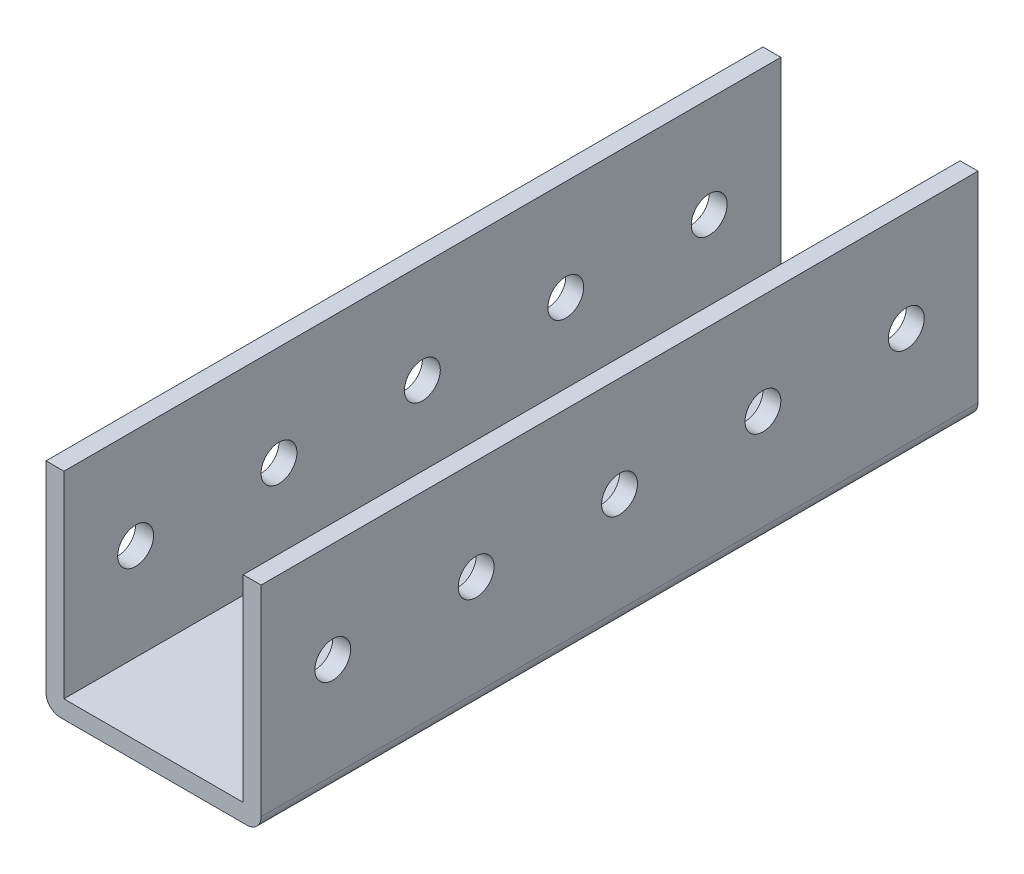
SolidWorks part; units mm, degrees
ref_plane "Front Plane" through (0, 0, 0) normal (0, 0, 1) x (1, 0, 0)
ref_plane "Top Plane" through (0, 0, 0) normal (0, 1, 0) x (1, 0, 0)
ref_plane "Right Plane" through (0, 0, 0) normal (1, 0, 0) x (0, 0, -1)
sketch "Sketch2" plane through (0, 0, 0) normal (0, 1, 0) x (1, 0, 0)
  line L1 (-19.05, -63.5) -> (19.05, -63.5)
  line L2 (-19.05, -63.5) -> (-19.05, 63.5)
  line L3 (-19.05, 63.5) -> (19.05, 63.5)
  line L4 (19.05, -63.5) -> (19.05, 63.5)
  line L5 (-19.05, -63.5) -> (19.05, 63.5) construction
  line L6 (-19.05, 63.5) -> (19.05, -63.5) construction
  point P0 (0, 0)
  dimension "D1" = 38.1
  dimension "D2" = 127
extrude "Boss-Extrude1" add sketch "Sketch2" along normal blind 38.1
sketch "Sketch3" plane through (0, 0, 63.5) normal (0, 0, 1) x (1, 0, 0)
  line L0 (-19.05, 38.1) -> (19.05, 38.1) construction
  line L1 (-15.875, 38.1) -> (15.875, 38.1)
  line L2 (-15.875, 38.1) -> (-15.875, 3.175)
  line L3 (-15.875, 3.175) -> (15.875, 3.175)
  line L4 (15.875, 38.1) -> (15.875, 3.175)
  line L5 (-19.05, 38.1) -> (-19.05, 0) construction
  line L6 (19.05, 38.1) -> (19.05, 0) construction
  line L7 (-19.05, 0) -> (19.05, 0) construction
  dimension "D1" = 3.175
  dimension "D2" = 3.175
  dimension "D3" = 3.175
extrude "Cut-Extrude1" cut sketch "Sketch3" against normal blind 406.4
fillet "Fillet1" radius 2.54 2 edges at (-19.05, 0, 0) (19.05, 0, 0)
sketch "Sketch4" plane through (19.05, 0, 0) normal (1, 0, 0) x (0, 0, -1)
  line L1 (-63.5, 38.1) -> (-63.5, 2.54) construction
  line L5 (-63.5, 2.54) -> (63.5, 2.54) construction
  circle A0 centre (-50.8, 20.32) radius 3.175
  circle A1 centre (-25.4, 20.32) radius 3.175
  circle A2 centre (0, 20.32) radius 3.175
  circle A3 centre (25.4, 20.32) radius 3.175
  circle A4 centre (50.8, 20.32) radius 3.175
  dimension "D1" = 6.35
  dimension "D2" = 17.78
  dimension "D3" = 12.7
  dimension "D4" = 5
extrude "Cut-Extrude2" cut sketch "Sketch4" against normal blind 50.8
